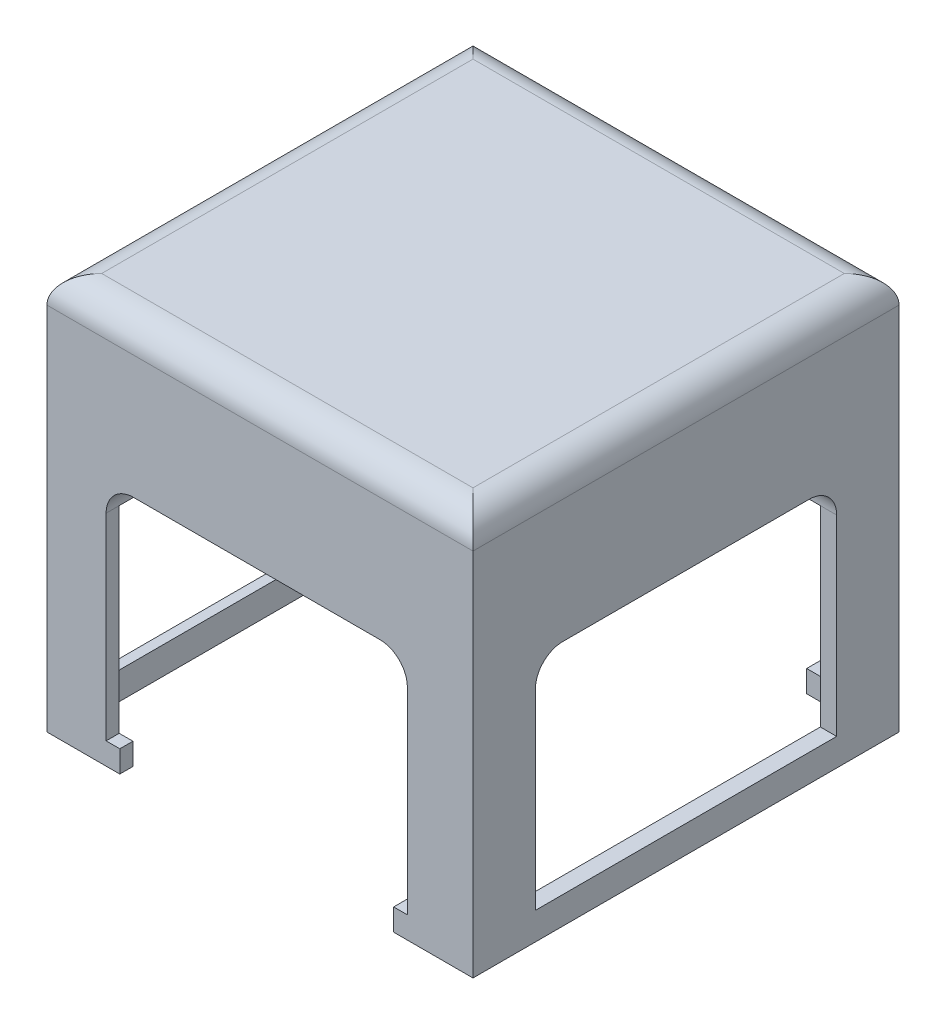
SolidWorks part; units mm, degrees
ref_plane "Front Plane" through (0, 0, 0) normal (0, 0, 1) x (1, 0, 0)
ref_plane "Top Plane" through (0, 0, 0) normal (0, 1, 0) x (1, 0, 0)
ref_plane "Right Plane" through (0, 0, 0) normal (1, 0, 0) x (0, 0, -1)
sketch "Sketch1" plane through (0, 0, 0) normal (0, 1, 0) x (1, 0, 0)
  line L1 (-77.79, 77.79) -> (77.79, 77.79)
  line L2 (-77.79, 77.79) -> (-77.79, -77.79)
  line L3 (-77.79, -77.79) -> (77.79, -77.79)
  line L4 (77.79, 77.79) -> (77.79, -77.79)
  line L5 (-77.79, 77.79) -> (77.79, -77.79) construction
  line L6 (-77.79, -77.79) -> (77.79, 77.79) construction
  point P0 (0, 0)
  dimension "D1" = 155.58
  dimension "D2" = 155.58
extrude "Boss-Extrude1" add sketch "Sketch1" along normal blind 145
sketch "Sketch2" plane through (0, 0, 77.79) normal (0, 0, 1) x (1, 0, 0)
  line L0 (-77.79, 72.5) -> (77.79, 72.5) construction
  line L3 (-77.79, 145) -> (-77.79, 0) construction
  line L4 (77.79, 145) -> (77.79, 0) construction
  line L5 (-1.177, 53.75) -> (-1.177, 36.25) construction
  line L7 (-1.177, 36.25) -> (-77.79, 36.25) construction
  line L9 (-1.177, 53.75) -> (-77.79, 53.75) construction
  line L10 (-77.79, 0) -> (77.79, 0) construction
  line L11 (-46.177, 90) -> (43.823, 90)
  line L12 (-56.177, 80) -> (-56.177, 0)
  line L13 (-56.177, 0) -> (53.823, 0)
  line L14 (53.823, 80) -> (53.823, 0)
  line L15 (-56.177, 90) -> (53.823, 0) construction
  line L16 (-56.177, 0) -> (53.823, 90) construction
  line L17 (53.823, 8) -> (48.823, 8)
  line L18 (-56.177, 0) -> (-51.177, 0)
  line L19 (-56.177, 0) -> (-56.177, 8)
  line L20 (-56.177, 8) -> (-51.177, 8)
  line L21 (-51.177, 0) -> (-51.177, 8)
  line L22 (48.823, 0) -> (48.823, 8)
  line L23 (53.823, 0) -> (48.823, 0)
  line L24 (53.823, 0) -> (53.823, 8)
  arc A0 (43.823, 90) -> (53.823, 80) centre (43.823, 80) cw
  arc A1 (-46.177, 90) -> (-56.177, 80) centre (-46.177, 80) ccw
  point P7 (-1.177, 45)
  dimension "D3" = 10
  dimension "D1" = 110
  dimension "D2" = 90
  dimension "D4" = 5
  dimension "D5" = 8
extrude "Cut-Extrude1" cut sketch "Sketch2" against normal up to next contours L11 A1 L12 L20 L21 L13 L22 L17 L14 A0
sketch "Sketch3" plane through (77.79, 0, 0) normal (1, 0, 0) x (0, 0, -1)
  line L1 (-77.79, 145) -> (-77.79, 0) construction
  line L2 (-55, 0) -> (55, 0)
  line L3 (0, 53.75) -> (0, 36.25) construction
  line L4 (0, 36.25) -> (-77.79, 36.25) construction
  line L5 (-55, 0) -> (-55, 10)
  line L6 (-77.79, 0) -> (77.79, 0) construction
  line L11 (-45, 90) -> (45, 90)
  line L12 (-55, 80) -> (-55, 0)
  line L13 (-55, 0) -> (55, 0)
  line L14 (55, 80) -> (55, 0)
  line L15 (-55, 90) -> (55, 0) construction
  line L16 (-55, 0) -> (55, 90) construction
  line L17 (-55, 10) -> (55, 10)
  line L18 (55, 0) -> (55, 10)
  arc A2 (45, 90) -> (55, 80) centre (45, 80) cw
  arc A3 (-45, 90) -> (-55, 80) centre (-45, 80) ccw
  point P7 (0, 50.3125)
  point P12 (0, 45)
  point P19 (-55, 40)
  dimension "D4" = 10
  dimension "D1" = 110
  dimension "D2" = 90
  dimension "D3" = 22.79
  dimension "D5" = 10
  dimension "D6" = 110
extrude "Cut-Extrude2" cut sketch "Sketch3" against normal blind 155.8 contours L11 A3 L12 L17 L14 A2
sketch "Sketch4" plane through (0, 0, 0) normal (0, -1, 0) x (1, 0, 0)
  line L0 (-1.177, 77.79) -> (-1.177, -77.79) construction
  line L1 (53.823, -55) -> (71.823, -55)
  line L2 (53.823, -55) -> (53.823, -73)
  line L3 (53.823, -73) -> (71.823, -73)
  line L4 (71.823, -55) -> (71.823, -73)
  line L5 (43.823, 77.79) -> (-46.177, 77.79) construction
  line L6 (-46.177, -77.79) -> (43.823, -77.79) construction
  line L7 (-77.79, 0) -> (77.79, 0) construction
  line L8 (-77.79, -45) -> (-77.79, 45) construction
  line L9 (77.79, -45) -> (77.79, 45) construction
  line L10 (-56.177, -73) -> (-74.177, -73)
  line L11 (-74.177, -55) -> (-74.177, -73)
  line L12 (-56.177, -55) -> (-74.177, -55)
  line L13 (-56.177, -55) -> (-56.177, -73)
  line L14 (53.823, 73) -> (71.823, 73)
  line L15 (71.823, 55) -> (71.823, 73)
  line L16 (53.823, 55) -> (71.823, 55)
  line L17 (53.823, 55) -> (53.823, 73)
  line L18 (-56.177, 55) -> (-56.177, 73)
  line L19 (-56.177, 55) -> (-74.177, 55)
  line L20 (-74.177, 55) -> (-74.177, 73)
  line L21 (-56.177, 73) -> (-74.177, 73)
  dimension "D1" = 18
  dimension "D2" = 18
extrude "Cut-Extrude3" cut sketch "Sketch4" against normal blind 80
fillet "Fillet1" radius 10 4 edges at (0, 145, 77.79) (77.79, 145, 0) (0, 145, -77.79) (-77.79, 145, 0)
sketch "Sketch5" plane through (0, 0, 0) normal (0, -1, 0) x (1, 0, 0)
  line L0 (-1.177, 77.79) -> (-1.177, -77.79) construction
  line L1 (-74.177, 55) -> (-56.177, 55)
  line L2 (-74.177, 55) -> (-74.177, -55)
  line L3 (-74.177, -55) -> (-56.177, -55)
  line L4 (-56.177, 55) -> (-56.177, -55)
  line L5 (43.823, 77.79) -> (-46.177, 77.79) construction
  line L6 (-46.177, -77.79) -> (43.823, -77.79) construction
  line L7 (71.823, -55) -> (53.823, -55)
  line L8 (53.823, 55) -> (53.823, -55)
  line L9 (71.823, 55) -> (53.823, 55)
  line L10 (71.823, 55) -> (71.823, -55)
extrude "Cut-Extrude4" cut sketch "Sketch5" against normal blind 10
sketch "Sketch6" plane through (0, 0, 0) normal (0, -1, 0) x (1, 0, 0)
  line L5 (53.823, 73) -> (-56.177, 73)
  line L6 (53.823, 73) -> (53.823, -73)
  line L7 (53.823, -73) -> (-56.177, -73)
  line L8 (-56.177, 73) -> (-56.177, -73)
extrude "Cut-Extrude5" cut sketch "Sketch6" against normal blind 10
